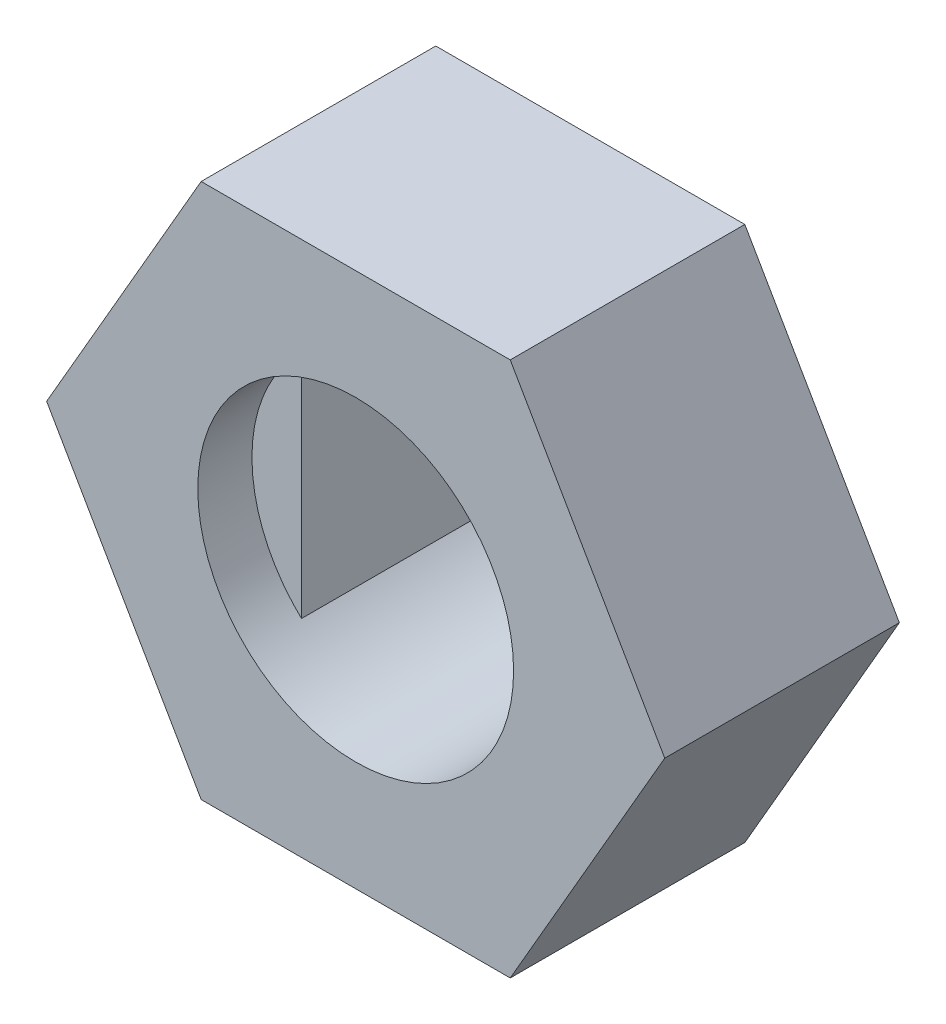
SolidWorks part; units mm, degrees
ref_plane "Front Plane" through (0, 0, 0) normal (0, 0, 1) x (1, 0, 0)
ref_plane "Top Plane" through (0, 0, 0) normal (0, 1, 0) x (1, 0, 0)
ref_plane "Right Plane" through (0, 0, 0) normal (1, 0, 0) x (0, 0, -1)
sketch "Sketch1" plane through (0, 0, 0) normal (0, 0, 1) x (1, 0, 0)
  line L1 (6.85, 0) -> (3.425, 5.9323)
  line L2 (3.425, 5.9323) -> (-3.425, 5.9323)
  line L3 (-3.425, 5.9323) -> (-6.85, 0)
  line L4 (-6.85, 0) -> (-3.425, -5.9323)
  line L5 (-3.425, -5.9323) -> (3.425, -5.9323)
  line L6 (3.425, -5.9323) -> (6.85, 0)
  circle A0 centre (0, 0) radius 5.9323 construction
  circle A1 centre (0, 0) radius 3.5
  dimension "D2" = 7
  dimension "D1" = 13.7
extrude "Boss-Extrude1" add sketch "Sketch1" along normal blind 5.2
sketch "Sketch2" plane through (0, 0, 0) normal (0, 0, -1) x (-1, 0, 0)
  line L0 (2.4, 2.5475) -> (2.4, -2.5475)
  line L1 (0, 2.513) -> (0, -1.3651) construction
  line L2 (-2.4, 2.5475) -> (-2.4, -2.5475)
  arc A0 (-2.4, 2.5475) -> (-2.4, -2.5475) centre (0, 0) ccw
  circle A1 centre (0, 0) radius 3.5 construction
  arc A2 (2.4, -2.5475) -> (2.4, 2.5475) centre (0, 0) ccw
  dimension "D1" = 4.8
extrude "Boss-Extrude2" add sketch "Sketch2" against normal blind 4 separate body
